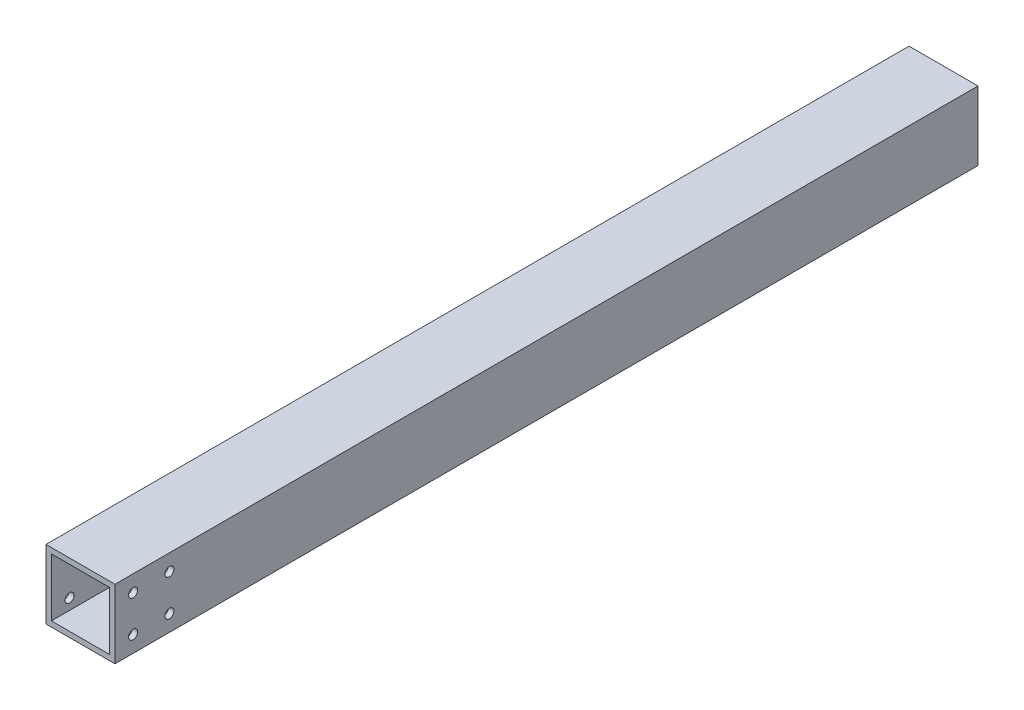
SolidWorks part; units mm, degrees
material "6061-T6 (SS)"
ref_plane "Front Plane" through (0, 0, 0) normal (0, 0, 1) x (1, 0, 0)
ref_plane "Top Plane" through (0, 0, 0) normal (0, 1, 0) x (1, 0, 0)
ref_plane "Right Plane" through (0, 0, 0) normal (1, 0, 0) x (0, 0, -1)
sketch "Sketch1" plane through (0, 0, 0) normal (0, 0, 1) x (1, 0, 0)
  line L0 (-16, 16) -> (16, 16)
  line L1 (-19, -19) -> (19, -19)
  line L2 (-19, -19) -> (-19, 19)
  line L3 (-19, 19) -> (19, 19)
  line L4 (19, -19) -> (19, 19)
  line L5 (-19, -19) -> (19, 19) construction
  line L6 (-19, 19) -> (19, -19) construction
  line L7 (16, -16) -> (16, 16)
  line L8 (-16, -16) -> (16, -16)
  line L9 (-16, -16) -> (-16, 16)
  point P0 (0, 0)
  dimension "D1" = 38
  dimension "D2" = 38
  dimension "D3" = 3
extrude "Boss-Extrude1" add sketch "Sketch1" along normal blind 475.6
sketch "Sketch3" plane through (19, 0, 0) normal (1, 0, 0) x (0, 0, -1)
  line L6 (-465.6, -10) -> (-445.6, -10) construction
  line L7 (-465.6, -10) -> (-465.6, 10) construction
  line L8 (-465.6, 10) -> (-445.6, 10) construction
  line L9 (-445.6, -10) -> (-445.6, 10) construction
  line L10 (-465.6, -10) -> (-445.6, 10) construction
  line L11 (-465.6, 10) -> (-445.6, -10) construction
  line L12 (-475.6, -19) -> (-475.6, 19) construction
  circle A4 centre (-465.6, 10) radius 2.5
  circle A5 centre (-445.6, 10) radius 2.5
  circle A6 centre (-445.6, -10) radius 2.5
  circle A7 centre (-465.6, -10) radius 2.5
  point P9 (-455.6, 0)
  point P20 (-465.6, 0)
  point P21 (-475.6, 0)
  dimension "D4" = 5
  dimension "D1" = 20
  dimension "D2" = 20
  dimension "D3" = 10
extrude "Cut-Extrude2" cut sketch "Sketch3" against normal through all both and the other way through all
